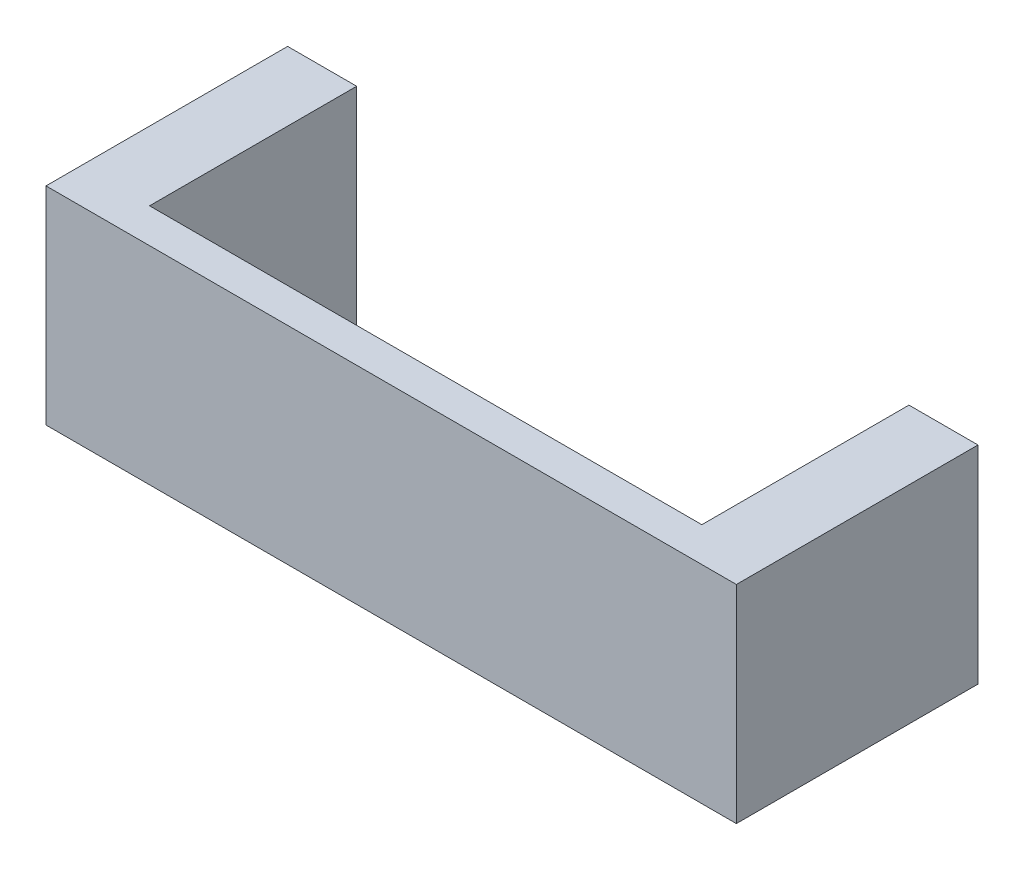
SolidWorks part; units mm, degrees
ref_plane "Přední rovina" through (0, 0, 0) normal (0, 0, 1) x (1, 0, 0)
ref_plane "Horní rovina" through (0, 0, 0) normal (0, 1, 0) x (1, 0, 0)
ref_plane "Pravá rovina" through (0, 0, 0) normal (1, 0, 0) x (0, 0, -1)
sketch "Sketch1" plane through (0, 0, 0) normal (0, 1, 0) x (1, 0, 0)
  line L1 (-50, 0) -> (-40, 0)
  line L2 (-50, 0) -> (-50, -35)
  line L3 (-50, -35) -> (50, -35)
  line L6 (-40, 0) -> (-40, -30)
  line L7 (-40, -30) -> (40, -30)
  line L9 (0, 0) -> (0, -35) construction
  line L10 (40, 0) -> (40, -30)
  line L11 (50, 0) -> (50, -35)
  line L12 (50, 0) -> (40, 0)
  point P3 (0, -30)
  dimension "D1" = 50
  dimension "D2" = 10
  dimension "D3" = 30
  dimension "D4" = 5
extrude "Boss-Extrude1" add sketch "Sketch1" along normal blind 30
